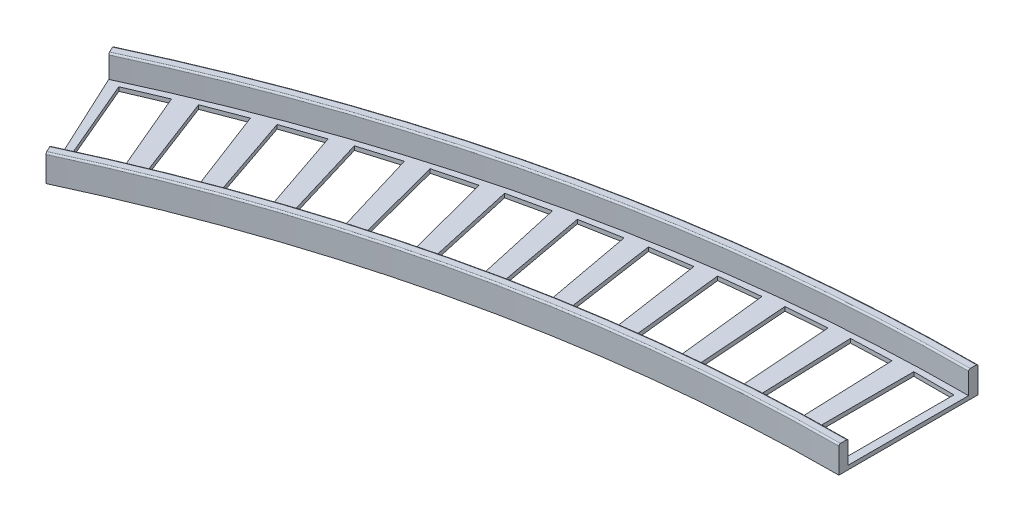
SolidWorks part; units mm, degrees
ref_plane "Front Plane" through (0, 0, 0) normal (0, 0, 1) x (1, 0, 0)
ref_plane "Top Plane" through (0, 0, 0) normal (0, 1, 0) x (1, 0, 0)
ref_plane "Right Plane" through (0, 0, 0) normal (1, 0, 0) x (0, 0, -1)
sketch "Sketch1" plane through (0, 0, 0) normal (1, 0, 0) x (0, 0, -1)
  line L0 (0, 0) -> (0, 17.2481) construction
  line L1 (-23.1, 10) -> (-25.4, 10)
  line L2 (-26, 9.4) -> (-26, 0)
  line L3 (-26, 0) -> (26, 0)
  line L4 (-22.5, 9.4) -> (-22.5, 1.5)
  line L5 (-22.5, 1.5) -> (22.5, 1.5)
  line L6 (22.5, 9.4) -> (22.5, 1.5)
  line L7 (26, 9.4) -> (26, 0)
  line L8 (23.1, 10) -> (25.4, 10)
  line L9 (-600, -3.3261) -> (-600, 49996.6739) construction
  arc A0 (-25.4, 10) -> (-26, 9.4) centre (-25.4, 9.4) ccw
  arc A1 (-22.5, 9.4) -> (-23.1, 10) centre (-23.1, 9.4) ccw
  arc A2 (26, 9.4) -> (25.4, 10) centre (25.4, 9.4) ccw
  arc A3 (22.5, 9.4) -> (23.1, 10) centre (23.1, 9.4) cw
  point P11 (0, 0)
  point P12 (0, 1.5)
  point P16 (-26, 10)
  point P19 (-22.5, 10)
  point P22 (26, 10)
  point P25 (22.5, 10)
  dimension "D5" = 0.6
  dimension "D6" = 0.6
  dimension "D1" = 52
  dimension "D2" = 3.5
  dimension "D3" = 10
  dimension "D4" = 1.5
  dimension "D7" = 600
revolve "Revolve1" add sketch "Sketch1" angle 25 about L9
sketch "Sketch4" plane through (0, 0, 0) normal (0, 1, 0) x (1, 0, 0)
  line L0 (0, 0) -> (0, -600) construction
  line L1 (-3, 20) -> (-18, 20)
  line L2 (-3, 20) -> (-3, -20)
  line L3 (-3, -20) -> (-18, -20)
  line L4 (-18, 20) -> (-18, -20)
  line L5 (0, -26) -> (0, 26) construction
  line L6 (-40.6088, 18.9305) -> (-39.1494, -21.0429)
  line L7 (-25.6188, 19.4777) -> (-24.1594, -20.4956)
  line L8 (-25.6188, 19.4777) -> (-40.6088, 18.9305)
  line L9 (-24.1594, -20.4956) -> (-39.1494, -21.0429)
  line L10 (-63.1635, 17.0368) -> (-60.2467, -22.8567)
  line L11 (-48.2035, 18.1306) -> (-45.2866, -21.7629)
  line L12 (-48.2035, 18.1306) -> (-63.1635, 17.0368)
  line L13 (-45.2866, -21.7629) -> (-60.2467, -22.8567)
  line L14 (-85.6342, 14.3214) -> (-81.2637, -25.4391)
  line L15 (-70.724, 15.9603) -> (-66.3535, -23.8002)
  line L16 (-70.724, 15.9603) -> (-85.6342, 14.3214)
  line L17 (-66.3535, -23.8002) -> (-81.2637, -25.4391)
  line L18 (-107.9908, 10.788) -> (-102.1725, -28.7866)
  line L19 (-93.1503, 12.9698) -> (-87.3321, -26.6048)
  line L20 (-93.1503, 12.9698) -> (-107.9908, 10.788)
  line L21 (-87.3321, -26.6048) -> (-102.1725, -28.7866)
  line L22 (-130.2035, 6.4413) -> (-122.9453, -32.8947)
  line L23 (-115.4526, 9.1631) -> (-108.1943, -30.1728)
  line L24 (-115.4526, 9.1631) -> (-130.2035, 6.4413)
  line L25 (-108.1943, -30.1728) -> (-122.9453, -32.8947)
  line L26 (-152.243, 1.287) -> (-143.5544, -37.7579)
  line L27 (-137.6011, 4.5452) -> (-128.9125, -34.4997)
  line L28 (-137.6011, 4.5452) -> (-152.243, 1.287)
  line L29 (-128.9125, -34.4997) -> (-143.5544, -37.7579)
  line L30 (-174.0796, -4.6679) -> (-163.9723, -43.3699)
  line L31 (-159.5664, -0.8777) -> (-149.4591, -39.5796)
  line L32 (-159.5664, -0.8777) -> (-174.0796, -4.6679)
  line L33 (-149.4591, -39.5796) -> (-163.9723, -43.3699)
  line L34 (-195.6845, -11.4156) -> (-184.1719, -49.723)
  line L35 (-181.3192, -7.0984) -> (-169.8066, -45.4058)
  line L36 (-181.3192, -7.0984) -> (-195.6845, -11.4156)
  line L37 (-169.8066, -45.4058) -> (-184.1719, -49.723)
  line L38 (-217.0288, -18.9471) -> (-204.1262, -56.809)
  line L39 (-202.8306, -14.1086) -> (-189.928, -51.9705)
  line L40 (-202.8306, -14.1086) -> (-217.0288, -18.9471)
  line L41 (-189.928, -51.9705) -> (-204.1262, -56.809)
  line L42 (-238.0841, -27.2523) -> (-223.8087, -64.6182)
  line L43 (-224.0719, -21.899) -> (-209.7965, -59.2649)
  line L44 (-224.0719, -21.899) -> (-238.0841, -27.2523)
  line L45 (-209.7965, -59.2649) -> (-223.8087, -64.6182)
  line L46 (-258.8224, -36.3202) -> (-243.1931, -73.1403)
  line L47 (-245.0148, -30.4592) -> (-229.3856, -67.2794)
  line L48 (-245.0148, -30.4592) -> (-258.8224, -36.3202)
  line L49 (-229.3856, -67.2794) -> (-243.1931, -73.1403)
  point P57 (0, -600)
  dimension "D1" = 600
  dimension "D2" = 3
  dimension "D3" = 15
  dimension "D4" = 40
  dimension "D5" = 20
  dimension "D6" = 12
extrude "Cut-Extrude3" cut sketch "Sketch4" along normal blind 10
